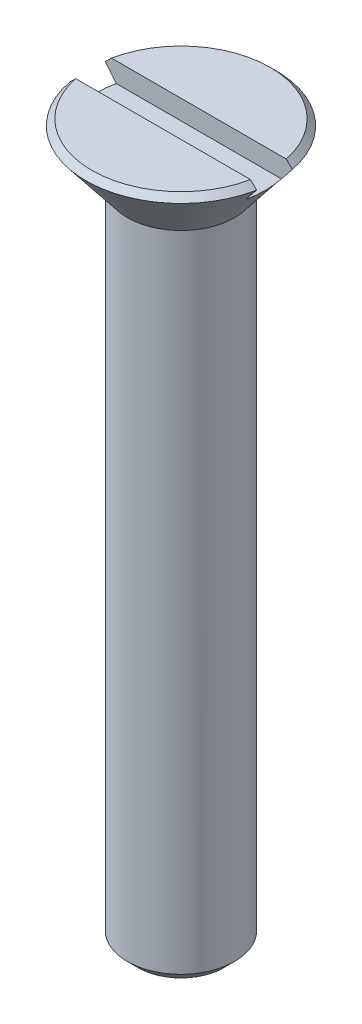
SolidWorks part; units mm, degrees
ref_plane "Front Plane" through (0, 0, 0) normal (0, 0, 1) x (1, 0, 0)
ref_plane "Top Plane" through (0, 0, 0) normal (0, 1, 0) x (1, 0, 0)
ref_plane "Right Plane" through (0, 0, 0) normal (1, 0, 0) x (0, 0, -1)
sketch "Sketch1" plane through (0, 0, 0) normal (0, 0, 1) x (1, 0, 0)
  line L0 (0, 0) -> (2.8, 0)
  line L1 (2.8, 0) -> (1.5, -1.65)
  line L2 (1.5, -1.65) -> (1.5, -20)
  line L3 (1.5, -20) -> (0, -20)
  line L4 (0, -20) -> (0, 0)
  line L5 (0, 0) -> (0, 4.4993) construction
  dimension "D1" = 20
  dimension "D2" = 3
  dimension "D3" = 1.65
  dimension "D4" = 5.6
revolve "Revolve1" add sketch "Sketch1" angle 360 about L5
chamfer "Chamfer1" distance 0.3 angle 45 1 edges at (0, -20, -1.5)
chamfer "Chamfer2" distance 0.3 angle 45 1 edges at (0, 0, -2.8)
sketch "Sketch2" plane through (0, 0, 0) normal (0, 1, 0) x (1, 0, 0)
  line L1 (-3.3, 0.5) -> (3.3, 0.5)
  line L2 (-3.3, 0.5) -> (-3.3, -0.5)
  line L3 (-3.3, -0.5) -> (3.3, -0.5)
  line L4 (3.3, 0.5) -> (3.3, -0.5)
  line L5 (-3.3, 0.5) -> (3.3, -0.5) construction
  line L6 (-3.3, -0.5) -> (3.3, 0.5) construction
  point P0 (0, 0)
  dimension "D1" = 6.6
  dimension "D2" = 1
extrude "Cut-Extrude1" cut sketch "Sketch2" against normal blind 0.55
equation "\"d\"= 3"
equation "\"dk\"= 5.6"
equation "\"k\"= 1.65"
equation "\"L\" = 20"
equation "\"D1@Sketch1\"=\"L\""
equation "\"D3@Sketch1\"=\"k\""
equation "\"D4@Sketch1\"=\"dk\""
equation "\"D1@Chamfer1\"=\"d\"/10"
equation "\"D1@Sketch2\"=\"dk\"+1"
equation "\"D2@Sketch2\"=\"d\"/3"
equation "\"D1@Cut-Extrude1\"=\"k\"/3"
equation "\"D1@Chamfer2\"=\"d\"/10"
